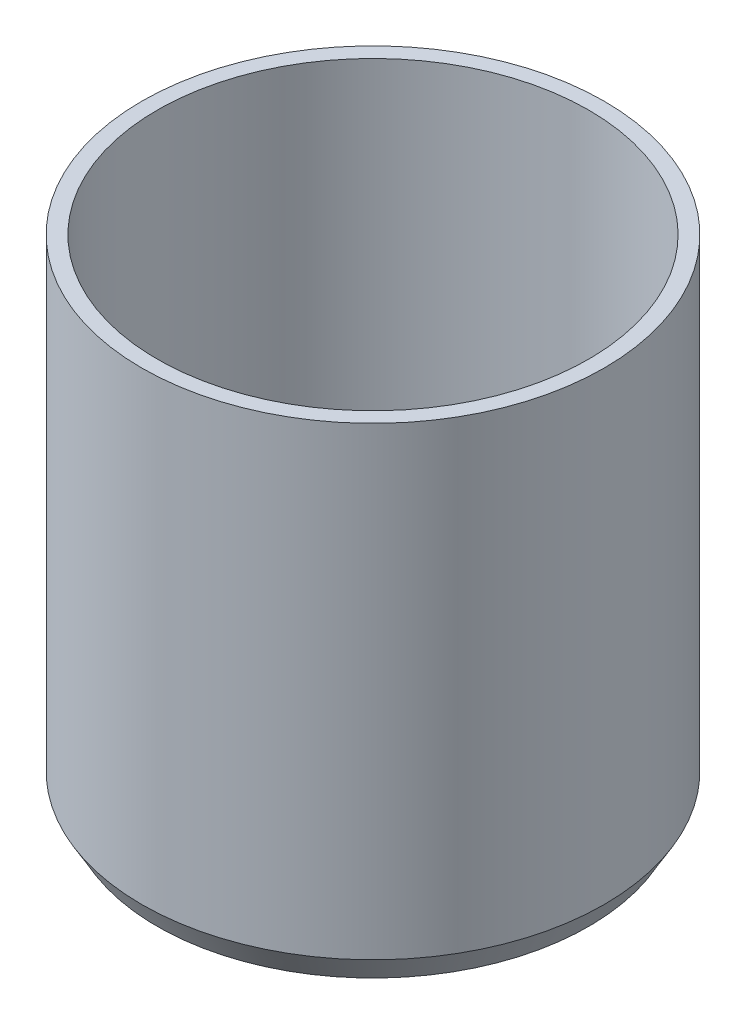
SolidWorks part; units mm, degrees
ref_plane "Front Plane" through (0, 0, 0) normal (0, 0, 1) x (1, 0, 0)
ref_plane "Top Plane" through (0, 0, 0) normal (0, 1, 0) x (1, 0, 0)
ref_plane "Right Plane" through (0, 0, 0) normal (1, 0, 0) x (0, 0, -1)
sketch "Sketch4" plane through (0, 0, 0) normal (0, 0, 1) x (1, 0, 0)
  line L0 (0, 0) -> (0, 237.6688) construction
  line L1 (0, 0) -> (70, 0)
  line L2 (70, 0) -> (75, 8.6603)
  line L3 (75, 8.6603) -> (75, 98.6603)
  line L5 (70, 98.6603) -> (70, 11.8281)
  line L6 (70, 11.8281) -> (67.4058, 5)
  line L7 (67.4058, 5) -> (0, 5)
  line L8 (0, 0) -> (0, 5)
  line L9 (75, 98.6603) -> (75, 159.3977)
  line L10 (75, 159.3977) -> (70, 159.3977)
  line L11 (70, 159.3977) -> (70, 98.6603)
  point P3 (72.5, 4.3301)
  dimension "D1" = 120
  dimension "D2" = 90
  dimension "D3" = 5
  dimension "D4" = 5
  dimension "D5" = 5
  dimension "D6" = 70
revolve "Revolve1" add sketch "Sketch4" angle 360 about L0
sketch3d "URDF Reference"
  line L0 (0, 0, 0) -> (10, 0, 0) construction
  line L1 (0, 0, 0) -> (0, 0, -10) construction
  point P0 (0, 0, 0)
  point P1 (0, 0, 0)
